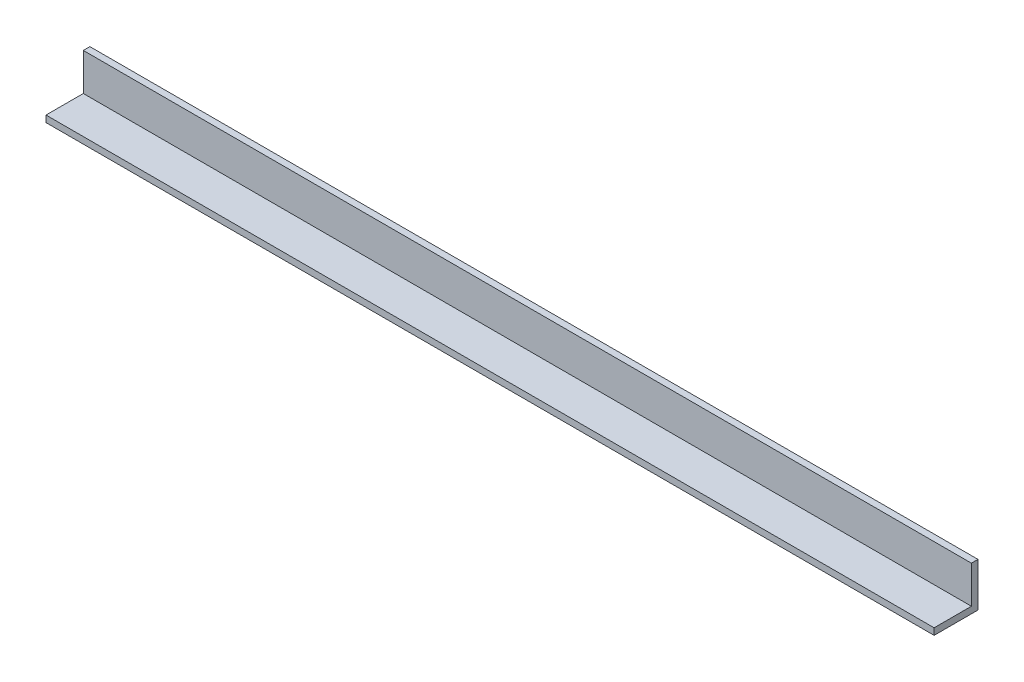
SolidWorks part; units mm, degrees
ref_plane "前视基准面" through (0, 0, 0) normal (0, 0, 1) x (1, 0, 0)
ref_plane "上视基准面" through (0, 0, 0) normal (0, 1, 0) x (1, 0, 0)
ref_plane "右视基准面" through (0, 0, 0) normal (1, 0, 0) x (0, 0, -1)
sketch "草图1" plane through (0, 0, 0) normal (0, 0, 1) x (1, 0, 0)
  line L1 (0, 0) -> (1619, 0)
  line L2 (0, 0) -> (0, 80)
  line L3 (0, 80) -> (1619, 80)
  line L4 (1619, 0) -> (1619, 80)
  dimension "D1" = 1619
  dimension "D2" = 80
extrude "拉伸1" add sketch "草图1" along normal blind 80
sketch "草图3" plane through (0, 0, 0) normal (-1, 0, 0) x (0, 0, 1)
  line L0 (80, 80) -> (80, 0) construction
  line L1 (12, 80) -> (80, 80)
  line L2 (12, 80) -> (12, 12)
  line L3 (12, 12) -> (80, 12)
  line L4 (80, 80) -> (80, 12)
  line L5 (80, 80) -> (0, 80) construction
  line L6 (80, 0) -> (0, 0) construction
  line L7 (0, 80) -> (0, 0) construction
  dimension "D1" = 12
  dimension "D2" = 12
extrude "拉伸2" cut sketch "草图3" against normal through all
